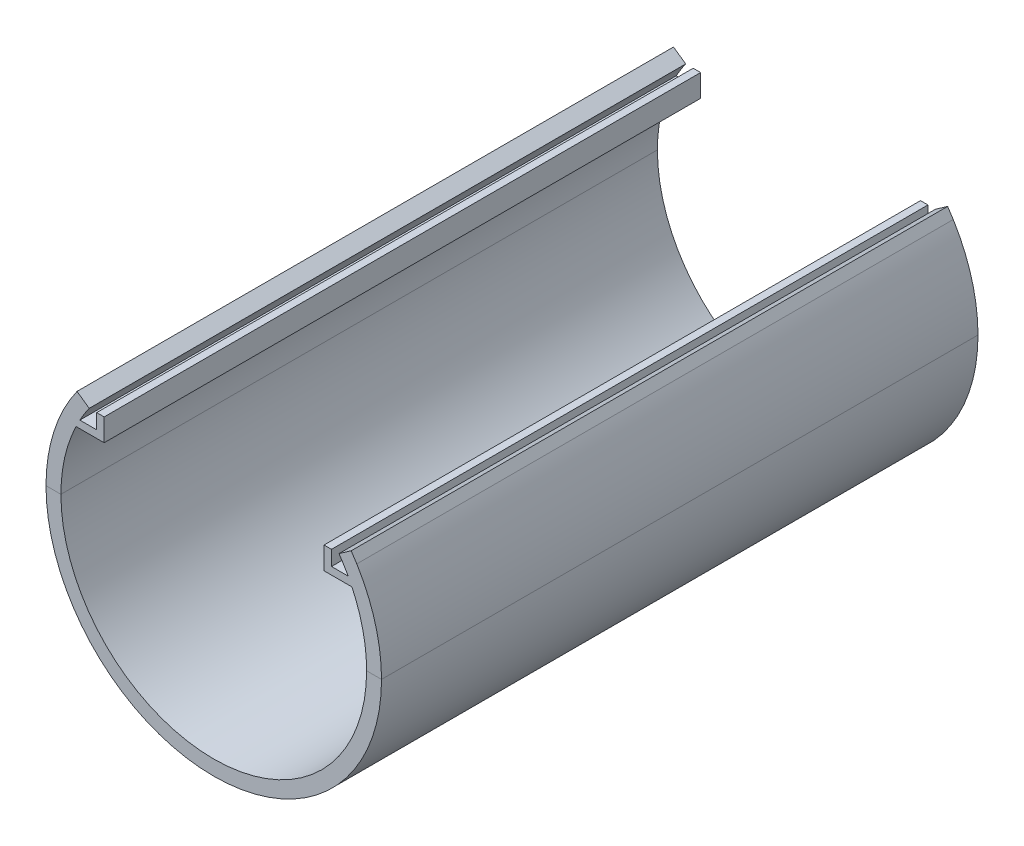
SolidWorks part; units mm, degrees
ref_plane "Front Plane" through (0, 0, 0) normal (0, 0, 1) x (1, 0, 0)
ref_plane "Top Plane" through (0, 0, 0) normal (0, 1, 0) x (1, 0, 0)
ref_plane "Right Plane" through (0, 0, 0) normal (1, 0, 0) x (0, 0, -1)
sketch "Sketch1" plane through (0, 0, 0) normal (0, 0, 1) x (1, 0, 0)
  circle A0 centre (0, 0) radius 22.5
  circle A1 centre (0, 0) radius 20.5
  dimension "D1" = 45
  dimension "D2" = 41
extrude "Boss-Extrude1" add sketch "Sketch1" along normal blind 80
sketch "Sketch2" plane through (0, 0, 80) normal (0, 0, 1) x (1, 0, 0)
  line L1 (-22.5, 0) -> (22.5, 0)
  line L2 (-22.5, 0) -> (-22.5, 22.5)
  line L3 (-22.5, 22.5) -> (22.5, 22.5)
  line L4 (22.5, 0) -> (22.5, 22.5)
  circle A0 centre (0, 0) radius 22.5 construction
extrude "Cut-Extrude1" cut sketch "Sketch2" against normal through all
sketch "Sketch4" plane through (0, 0, 80) normal (0, 0, 1) x (1, 0, 0)
  line L0 (19.1831, 11.7583) -> (18.4309, 12.9055)
  line L1 (16.7926, 11.7583) -> (18.4309, 12.9055)
  line L3 (20.5, 0) -> (22.5, 0)
  line L4 (16.7926, 11.7583) -> (19.1831, 11.7583)
  line L5 (18.4309, 12.9055) -> (16.7926, 11.7583)
  line L6 (15.7926, 11.7583) -> (15.7926, 9.7583)
  line L7 (19.1831, 11.7583) -> (14.7926, 11.7583)
  line L8 (19.1831, 11.7583) -> (19.1831, 8.7583)
  line L9 (19.1831, 8.7583) -> (14.7926, 8.7583)
  line L10 (14.7926, 11.7583) -> (14.7926, 8.7583)
  line L11 (15.7926, 9.7583) -> (18.0285, 9.7583)
  line L12 (16.7926, 11.7583) -> (15.7926, 11.7583)
  line L13 (14.7926, 8.7583) -> (18.5349, 8.7583)
  line L14 (14.7926, 8.7583) -> (14.7926, 11.7583)
  line L15 (14.7926, 11.7583) -> (16.7926, 11.7583)
  line L16 (-16.7023, 11.8863) -> (-18.3406, 13.0335)
  line L17 (-22.5, 0) -> (-20.5, 0) construction
  line L18 (-16.7023, 11.8863) -> (-15.7023, 11.8863)
  line L19 (-19.1041, 11.8863) -> (-14.7023, 11.8863)
  line L20 (-19.1041, 11.8863) -> (-19.1041, 8.8863)
  line L21 (-19.1041, 8.8863) -> (-14.7023, 8.8863)
  line L22 (-14.7023, 11.8863) -> (-14.7023, 8.8863)
  line L23 (-14.7023, 11.8863) -> (-15.7023, 11.8863)
  line L24 (-14.7023, 11.8863) -> (-14.7023, 8.8863)
  line L25 (-14.7023, 8.8863) -> (-15.7023, 8.8863)
  line L26 (-15.7023, 11.8863) -> (-15.7023, 8.8863)
  line L27 (-19.1041, 8.8863) -> (-14.7023, 8.8863)
  line L28 (-19.1041, 8.8863) -> (-19.1041, 9.8863)
  line L29 (-19.1041, 9.8863) -> (-14.7023, 9.8863)
  line L30 (-14.7023, 8.8863) -> (-14.7023, 9.8863)
  line L31 (-15.7023, 11.8863) -> (-15.7023, 9.8863)
  line L32 (-15.7023, 9.8863) -> (-17.9586, 9.8863)
  line L33 (-16.7023, 11.8863) -> (-15.7023, 11.1746)
  line L34 (-15.7023, 11.1746) -> (-15.7023, 9.8863)
  line L35 (-15.7023, 9.8863) -> (-17.9586, 9.8863)
  line L36 (-16.7023, 11.8863) -> (-19.1041, 11.8863)
  line L37 (-19.1041, 11.8863) -> (-19.1041, 8.8863)
  line L38 (-19.1041, 8.8863) -> (-18.4739, 8.8863)
  line L39 (-22.5, 0) -> (-20.5, 0)
  line L40 (-16.7023, 11.8863) -> (-15.7023, 11.8863)
  line L41 (-15.7023, 9.8863) -> (-17.9586, 9.8863)
  arc A0 (22.5, 0) -> (18.4309, 12.9055) centre (0, 0) ccw
  arc A1 (20.5, 0) -> (16.7926, 11.7583) centre (0, 0) ccw
  arc A2 (18.0285, 9.7583) -> (16.7926, 11.7583) centre (0, 0) ccw
  arc A3 (18.5349, 8.7583) -> (16.7926, 11.7583) centre (0, 0) ccw
  arc A4 (-22.5, 0) -> (-18.3406, 13.0335) centre (0, 0) cw
  arc A5 (-20.5, 0) -> (-16.7023, 11.8863) centre (0, 0) cw
  arc A6 (-17.9586, 9.8863) -> (-16.7023, 11.8863) centre (0, 0) cw
  arc A7 (-18.4739, 8.8863) -> (-16.7023, 11.8863) centre (0, 0) cw
  arc A8 (-17.9586, 9.8863) -> (-16.7023, 11.8863) centre (0, 0) cw
  line M11 (22.5, 0) -> (20.5, 0)
  dimension "D1" = 35
  dimension "D7" = 35
  dimension "D2" = 2
  dimension "D3" = 3
  dimension "D4" = 2
  dimension "D5" = 1
  dimension "D6" = 1
  dimension "D8" = 3
  dimension "D9" = 1
  dimension "D10" = 1
  dimension "D11" = 1
extrude "Boss-Extrude2" add sketch "Sketch4" against normal up to surface (80 mm away) separate body contours A1 A0 L8 L9 M11 | L1 L4 L0 | A1 L9 L8 L4 | L9 A1 L11 L6 L7 L10 | L16 A4 L39 A5 | L28 L27 L30 L29 | L24 L23 L26 L25 up to face at (0, -10.75, 0)
